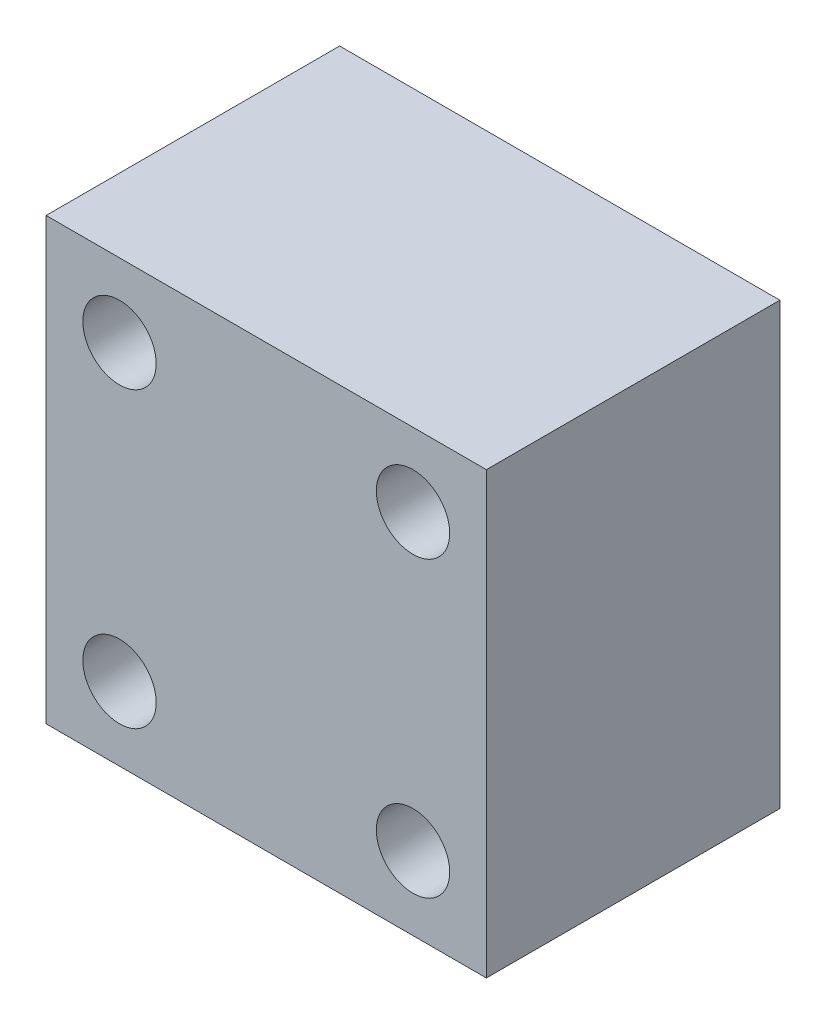
SolidWorks part; units mm, degrees
ref_plane "Front Plane" through (0, 0, 0) normal (0, 0, 1) x (1, 0, 0)
ref_plane "Top Plane" through (0, 0, 0) normal (0, 1, 0) x (1, 0, 0)
ref_plane "Right Plane" through (0, 0, 0) normal (1, 0, 0) x (0, 0, -1)
sketch "Sketch1" plane through (0, 0, 0) normal (0, 0, 1) x (1, 0, 0)
  line L1 (-24.502, 22.3506) -> (35.498, 22.3506)
  line L2 (-24.502, 22.3506) -> (-24.502, -37.6494)
  line L3 (-24.502, -37.6494) -> (35.498, -37.6494)
  line L4 (35.498, 22.3506) -> (35.498, -37.6494)
  dimension "D1" = 60
  dimension "D2" = 60
extrude "Boss-Extrude1" add sketch "Sketch1" along normal blind 40
sketch "Sketch2" plane through (0, 0, 40) normal (0, 0, 1) x (1, 0, 0)
  line L0 (-24.502, 22.3506) -> (-14.502, 22.3506)
  line L1 (35.498, 22.3506) -> (-24.502, 22.3506) construction
  line L2 (-14.502, 22.3506) -> (-14.502, 12.3506)
  line L3 (5.498, 22.3506) -> (5.498, -37.6494)
  line L4 (-24.502, -37.6494) -> (35.498, -37.6494) construction
  line L5 (5.498, -7.6494) -> (35.498, -7.6494)
  line L6 (35.498, -37.6494) -> (35.498, 22.3506) construction
  circle A0 centre (-14.502, 12.3506) radius 5
  circle A1 centre (25.498, 12.3506) radius 5
  circle A2 centre (25.498, -27.6494) radius 5
  circle A3 centre (-14.502, -27.6494) radius 5
  dimension "D1" = 10
  dimension "D2" = 10
extrude "Cut-Extrude1" cut sketch "Sketch2" against normal blind 20
